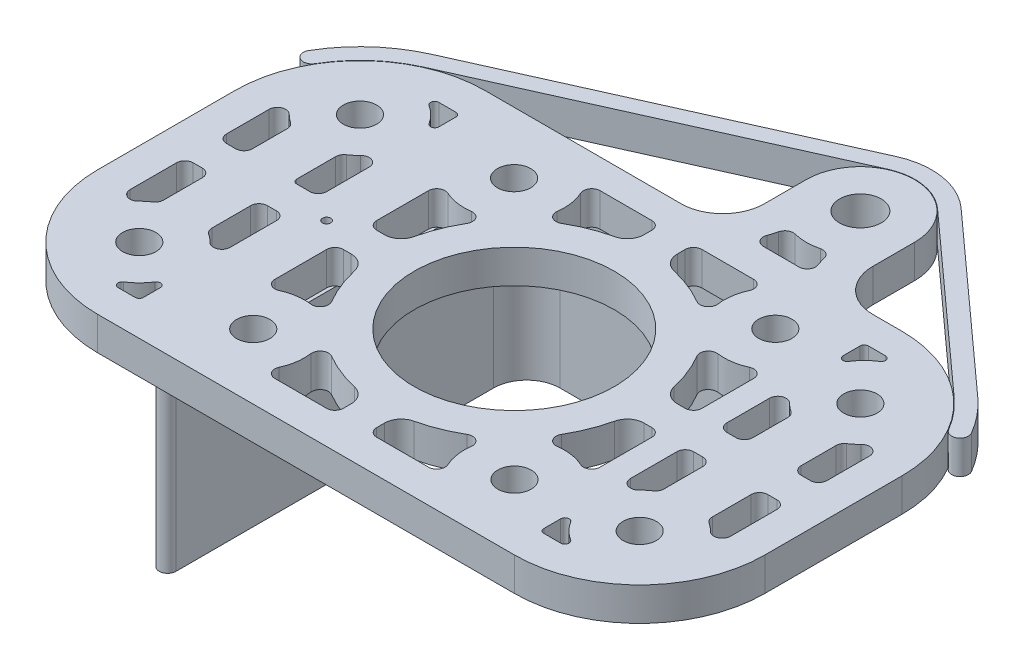
SolidWorks part; units mm, degrees
ref_plane "Front Plane" through (0, 0, 0) normal (0, 0, 1) x (1, 0, 0)
ref_plane "Top Plane" through (0, 0, 0) normal (0, 1, 0) x (1, 0, 0)
ref_plane "Right Plane" through (0, 0, 0) normal (1, 0, 0) x (0, 0, -1)
sketch "Sketch1" plane through (0, 0, 0) normal (0, 1, 0) x (1, 0, 0)
  line L1 (-21.5, 13.9196) -> (-21.5, 17.5) construction
  line L2 (-17.5, -21.5) -> (17.5, -21.5) construction
  line L3 (19.5, -3) -> (19.5, -9.2063)
  line L4 (19.5, 9.2063) -> (19.5, 3)
  line L5 (21.5, 21.5) -> (-21.5, -21.5) construction
  line L7 (-17.5, 21.5) -> (17.5, 21.5) construction
  line L8 (-11.4637, 10) -> (-11.4637, -10) construction
  line L9 (-11.4637, 10) -> (-11.4637, -10) construction
  line L10 (0, 0) -> (0, 15.6621) construction
  line L11 (0, 15.6621) -> (-15.6378, 15.6621) construction
  line L13 (-26.5, -23) -> (-3, -23)
  line L14 (0, -21.5) -> (0, 38.5) construction
  line L15 (-26.5, 23.4637) -> (23.5, 23.4637)
  line L16 (38.5, -8) -> (38.5, 8.4637)
  line L17 (21.5, -17.5) -> (21.5, 17.5) construction
  line L18 (-41.5, 8.4637) -> (-41.5, -8)
  line L19 (-31.5, 7.4637) -> (-31.5, -7) construction
  line L21 (-21.5, -21.5) -> (21.5, 21.5) construction
  line L22 (18.5, 2) -> (17.5499, 2)
  line L23 (-34.4, 7.6508) -> (-34.4, 3)
  line L27 (-28.6, 7.6508) -> (-28.6, 3)
  line L28 (-25.5, 8.5647) -> (-25.5, 3)
  line L29 (-37.5, -8.101) -> (-37.5, -3)
  line L30 (18.5, -2) -> (17.5499, -2)
  line L31 (-3, -19.5) -> (-9.2063, -19.5)
  line L32 (9.2063, -19.5) -> (3, -19.5)
  line L33 (12.6, -23) -> (12.6, -43) construction
  line L34 (2, -18.5) -> (2, -17.5499)
  line L35 (-2, -18.5) -> (-2, -17.5499)
  line L36 (-19.5, 3) -> (-19.5, 9.2063)
  line L37 (-19.5, -9.2063) -> (-19.5, -3)
  line L38 (-18.5, -2) -> (-17.5499, -2)
  line L39 (-9.2063, 19.5) -> (-3, 19.5)
  line L40 (-25.5, 16.9278) -> (-25.5, 18.9637)
  line L41 (2, 18.5) -> (2, 17.5499)
  line L42 (-2, 18.5) -> (-2, 17.5499)
  line L43 (3, 19.5) -> (9.2063, 19.5)
  line L44 (0, 23.4637) -> (0, 16) construction
  line L45 (-18.5, 2) -> (-17.5499, 2)
  line L47 (18.5, 38.5) -> (38.5, 38.5) construction
  line L48 (-26.5, -2) -> (-28.1, -2)
  line L51 (-25.5, -16.4641) -> (-25.5, -18.5)
  line L52 (-20.3267, -20.3302) -> (-20.3284, -20.3284)
  line L53 (-28.0359, -19) -> (-26, -19)
  line L54 (0, -23.4637) -> (0, -16) construction
  line L55 (-21.5, 623) -> (-21.5, -43) construction
  line L56 (18.5, -23) -> (18.5, 603) construction
  line L57 (12.8901, -37.861) -> (33.5871, -19.1693)
  line L58 (-19.5, -23) -> (-15.6, -23) construction
  line L59 (5.8213, -38.9772) -> (-32.6549, -21.7339)
  line L60 (12.6, -43) -> (12.6, -63) construction
  line L61 (-18.9133, -18.9151) -> (-18.9142, -18.9142)
  line L62 (-26.5, 2) -> (-27.6, 2)
  line L63 (-21.5, 38.5) -> (-41.5, 38.5) construction
  line L65 (-28.0359, 19.4637) -> (-26, 19.4637)
  line L66 (23, -19.4637) -> (25.0359, -19.4637)
  line L67 (-34.4, -3) -> (-34.4, -7.1871)
  line L68 (-37.5, 3) -> (-37.5, 8.5647)
  line L69 (-35.4, 2) -> (-36.5, 2)
  line L70 (-35.4, -2) -> (-36.5, -2)
  line L71 (-28.6, -2.5) -> (-28.6, -7.1871)
  line L72 (-25.5, -3) -> (-25.5, -8.101)
  line L73 (22.5, -8.101) -> (22.5, -3)
  line L74 (28.5, 7.4637) -> (28.5, -7) construction
  line L75 (-26.5, -3) -> (-18.5, 3) construction
  line L76 (-31.5, 27.4637) -> (28.5, 27.4637) construction
  line L77 (-26.5, 3) -> (-18.5, -3) construction
  line L78 (22.5, 16.9278) -> (22.5, 18.9637)
  line L79 (34.5, -8.101) -> (34.5, -3)
  line L80 (25.6, 7.6508) -> (25.6, 3)
  line L81 (31.4, 7.6508) -> (31.4, 3)
  line L82 (23, 19.4637) -> (25.0359, 19.4637)
  line L83 (22.5, -16.9278) -> (22.5, -18.9637)
  line L84 (17.5499, 2) -> (17.5499, -2) construction
  line L85 (22.5, 0) -> (25.6, 0) construction
  line L86 (23.5, -2) -> (24.6, -2)
  line L87 (23.5, 2) -> (24.6, 2)
  line L88 (-31.5, 23.4637) -> (28.5, 23.4637) construction
  line L89 (15, -33) -> (15, -28)
  line L90 (32.4, -2) -> (33.5, -2)
  line L91 (25.6, -3) -> (25.6, -7.1871)
  line L92 (28.5, 38.5) -> (28.5, 26.8752) construction
  line L93 (31.4, -3) -> (31.4, -7.1871)
  line L94 (32.4, 2) -> (33.5, 2)
  line L95 (22.5, 3) -> (22.5, 8.5647)
  line L96 (34.5, 3) -> (34.5, 8.5647)
  line L97 (2, -33) -> (2, -28)
  line L98 (20, -23) -> (23.5, -23)
  line L100 (5.0034, -40.8023) -> (-33.4728, -23.559)
  line L101 (10.6325, -23.5) -> (6.3675, -23.5)
  line L102 (14.2306, -39.3453) -> (34.9276, -20.6536)
  line L103 (9.2063, -23.5) -> (3, -23.5) construction
  arc A0 (23.5, -23) -> (38.5, -8) centre (23.5, -8) ccw
  arc A1 (38.5, 8.4637) -> (23.5, 23.4637) centre (23.5, 8.4637) ccw
  arc A2 (-26.5, 23.4637) -> (-41.5, 8.4637) centre (-26.5, 8.4637) ccw
  arc A3 (-17.5, 21.5) -> (-21.5, 17.5) centre (-17.5, 17.5) ccw construction
  arc A4 (-21.5, -17.5) -> (-17.5, -21.5) centre (-17.5, -17.5) ccw construction
  arc A5 (-41.5, -8) -> (-26.5, -23) centre (-26.5, -8) ccw
  circle A7 centre (-31.5, 13.4637) radius 2
  circle A9 centre (28.5, 13.4637) radius 2
  circle A10 centre (0, 0) radius 12
  circle A11 centre (-15.6378, 15.6621) radius 2
  circle A12 centre (15.6621, 15.6378) radius 2
  circle A13 centre (0, 0) radius 3.7
  arc A14 (21.5, -17.5) -> (17.5, -21.5) centre (17.5, -17.5) cw construction
  arc A15 (17.5, 21.5) -> (21.5, 17.5) centre (17.5, 17.5) cw construction
  circle A20 centre (15.6378, -15.6621) radius 2
  circle A21 centre (-15.6621, -15.6378) radius 2
  circle A22 centre (28.5, -13) radius 2
  circle A23 centre (-31.5, -13) radius 2
  arc A24 (-28.1571, 8.4812) -> (-27.2143, 9.2646) centre (-31.5, 13.4637) ccw
  arc A25 (-34.8429, -8.0175) -> (-35.7857, -8.8009) centre (-31.5, -13) ccw
  arc A26 (31.8429, 8.4812) -> (32.7857, 9.2646) centre (28.5, 13.4637) ccw
  arc A27 (25.1571, -8.0175) -> (24.2143, -8.8009) centre (28.5, -13) ccw
  arc A28 (-26.4231, 16.6614) -> (-28.3024, 18.5406) centre (-31.5, 13.4637) ccw
  arc A29 (-27.2143, -8.8009) -> (-28.1571, -8.0175) centre (-31.5, -13) ccw
  arc A30 (-35.7857, 9.2646) -> (-34.8429, 8.4812) centre (-31.5, 13.4637) ccw
  arc A31 (-28.3024, -18.0769) -> (-26.4231, -16.1976) centre (-31.5, -13) ccw
  arc A32 (13.7831, -8.1256) -> (15.5999, -3.5556) centre (0, 0) ccw
  arc A33 (13.7831, -8.1256) -> (14.7756, -9.6248) centre (14.6446, -8.6335) ccw
  arc A34 (18.0864, -10.1167) -> (14.7756, -9.6248) centre (15.5724, -15.6501) ccw
  arc A35 (17.5499, -2) -> (15.5999, -3.5556) centre (17.5499, -4) ccw
  arc A36 (18.0864, -10.1167) -> (19.5, -9.2063) centre (18.5, -9.2063) ccw
  arc A37 (19.5, -3) -> (18.5, -2) centre (18.5, -3) ccw
  arc A38 (18.0864, 10.1167) -> (14.7756, 9.6248) centre (15.5724, 15.6501) cw
  arc A39 (17.5499, 2) -> (15.5999, 3.5556) centre (17.5499, 4) cw
  arc A40 (13.7831, 8.1256) -> (14.7756, 9.6248) centre (14.6446, 8.6335) cw
  arc A41 (13.7831, 8.1256) -> (15.5999, 3.5556) centre (0, 0) cw
  arc A42 (18.5, 2) -> (19.5, 3) centre (18.5, 3) ccw
  arc A43 (18.0864, 10.1167) -> (19.5, 9.2063) centre (18.5, 9.2063) cw
  arc A44 (-8.1256, -13.7831) -> (-3.5556, -15.5999) centre (0, 0) ccw
  arc A45 (-10.1167, 18.0864) -> (-9.6248, 14.7756) centre (-15.6501, 15.5724) cw
  arc A46 (8.1256, 13.7831) -> (3.5556, 15.5999) centre (0, 0) ccw
  arc A47 (-8.1256, -13.7831) -> (-9.6248, -14.7756) centre (-8.6335, -14.6446) ccw
  arc A48 (8.1256, 13.7831) -> (9.6248, 14.7756) centre (8.6335, 14.6446) ccw
  arc A49 (10.1167, 18.0864) -> (9.6248, 14.7756) centre (15.6501, 15.5724) ccw
  arc A50 (2, 17.5499) -> (3.5556, 15.5999) centre (4, 17.5499) ccw
  arc A51 (-2, 17.5499) -> (-3.5556, 15.5999) centre (-4, 17.5499) cw
  arc A52 (-10.1167, -18.0864) -> (-9.6248, -14.7756) centre (-15.6501, -15.5724) ccw
  arc A53 (-8.1256, 13.7831) -> (-9.6248, 14.7756) centre (-8.6335, 14.6446) cw
  arc A54 (-2, -17.5499) -> (-3.5556, -15.5999) centre (-4, -17.5499) ccw
  arc A55 (-8.1256, 13.7831) -> (-3.5556, 15.5999) centre (0, 0) cw
  arc A56 (-10.1167, -18.0864) -> (-9.2063, -19.5) centre (-9.2063, -18.5) ccw
  arc A57 (-3, -19.5) -> (-2, -18.5) centre (-3, -18.5) ccw
  arc A58 (10.1167, -18.0864) -> (9.6248, -14.7756) centre (15.6501, -15.5724) cw
  arc A59 (2, -17.5499) -> (3.5556, -15.5999) centre (4, -17.5499) cw
  arc A60 (8.1256, -13.7831) -> (9.6248, -14.7756) centre (8.6335, -14.6446) cw
  arc A61 (8.1256, -13.7831) -> (3.5556, -15.5999) centre (0, 0) cw
  arc A62 (2, -18.5) -> (3, -19.5) centre (3, -18.5) ccw
  arc A63 (10.1167, -18.0864) -> (9.2063, -19.5) centre (9.2063, -18.5) cw
  arc A64 (-13.7831, 8.1256) -> (-15.5999, 3.5556) centre (0, 0) ccw
  arc A65 (-13.7831, 8.1256) -> (-14.7756, 9.6248) centre (-14.6446, 8.6335) ccw
  arc A66 (-18.0864, 10.1167) -> (-14.7756, 9.6248) centre (-15.5724, 15.6501) ccw
  arc A67 (-17.5499, 2) -> (-15.5999, 3.5556) centre (-17.5499, 4) ccw
  arc A68 (-18.0864, 10.1167) -> (-19.5, 9.2063) centre (-18.5, 9.2063) ccw
  arc A69 (-19.5, 3) -> (-18.5, 2) centre (-18.5, 3) ccw
  arc A70 (-18.0864, -10.1167) -> (-14.7756, -9.6248) centre (-15.5724, -15.6501) cw
  arc A71 (-17.5499, -2) -> (-15.5999, -3.5556) centre (-17.5499, -4) cw
  arc A72 (-13.7831, -8.1256) -> (-14.7756, -9.6248) centre (-14.6446, -8.6335) cw
  arc A73 (10.1167, 18.0864) -> (9.2063, 19.5) centre (9.2063, 18.5) ccw
  arc A74 (-13.7831, -8.1256) -> (-15.5999, -3.5556) centre (0, 0) cw
  arc A75 (-18.5, -2) -> (-19.5, -3) centre (-18.5, -3) ccw
  arc A76 (3, 19.5) -> (2, 18.5) centre (3, 18.5) ccw
  arc A77 (-18.0864, -10.1167) -> (-19.5, -9.2063) centre (-18.5, -9.2063) cw
  arc A78 (-2, 18.5) -> (-3, 19.5) centre (-3, 18.5) ccw
  arc A79 (-28.6, -7.1871) -> (-28.1571, -8.0175) centre (-27.6, -7.1871) ccw
  arc A80 (-10.1167, 18.0864) -> (-9.2063, 19.5) centre (-9.2063, 18.5) cw
  arc A81 (-25.5, -8.101) -> (-27.2143, -8.8009) centre (-26.5, -8.101) cw
  arc A82 (-37.5, -8.101) -> (-35.7857, -8.8009) centre (-36.5, -8.101) ccw
  arc A83 (-34.4, -7.1871) -> (-34.8429, -8.0175) centre (-35.4, -7.1871) cw
  arc A84 (-34.4, 7.6508) -> (-34.8429, 8.4812) centre (-35.4, 7.6508) ccw
  arc A85 (-28.6, 7.6508) -> (-28.1571, 8.4812) centre (-27.6, 7.6508) cw
  arc A86 (-25.5, 8.5647) -> (-27.2143, 9.2646) centre (-26.5, 8.5647) ccw
  arc A87 (-37.5, 8.5647) -> (-35.7857, 9.2646) centre (-36.5, 8.5647) cw
  arc A88 (24.6, -2) -> (25.6, -3) centre (24.6, -3) cw
  arc A89 (23.5, -2) -> (22.5, -3) centre (23.5, -3) ccw
  arc A90 (32.7857, -8.8009) -> (31.8429, -8.0175) centre (28.5, -13) ccw
  arc A91 (25.3024, 18.5406) -> (23.4231, 16.6614) centre (28.5, 13.4637) ccw
  arc A92 (25.6, -7.1871) -> (25.1571, -8.0175) centre (24.6, -7.1871) cw
  arc A93 (22.5, -8.101) -> (24.2143, -8.8009) centre (23.5, -8.101) ccw
  arc A94 (32.4, -2) -> (31.4, -3) centre (32.4, -3) ccw
  arc A95 (34.5, -3) -> (33.5, -2) centre (33.5, -3) ccw
  arc A96 (31.4, -7.1871) -> (31.8429, -8.0175) centre (32.4, -7.1871) ccw
  arc A97 (34.5, -8.101) -> (32.7857, -8.8009) centre (33.5, -8.101) cw
  arc A98 (34.5, 3) -> (33.5, 2) centre (33.5, 3) cw
  arc A99 (31.4, 7.6508) -> (31.8429, 8.4812) centre (32.4, 7.6508) cw
  arc A100 (34.5, 8.5647) -> (32.7857, 9.2646) centre (33.5, 8.5647) ccw
  arc A101 (31.4, 3) -> (32.4, 2) centre (32.4, 3) ccw
  arc A102 (23.5, 2) -> (22.5, 3) centre (23.5, 3) cw
  arc A103 (24.6, 2) -> (25.6, 3) centre (24.6, 3) ccw
  arc A104 (25.6, 7.6508) -> (25.1571, 8.4812) centre (24.6, 7.6508) ccw
  arc A105 (22.5, 8.5647) -> (24.2143, 9.2646) centre (23.5, 8.5647) cw
  arc A106 (24.2143, 9.2646) -> (25.1571, 8.4812) centre (28.5, 13.4637) ccw
  arc A107 (25.3024, -18.5406) -> (23.4231, -16.6614) centre (28.5, -13.4637) cw
  arc A108 (-27.6, 2) -> (-28.6, 3) centre (-27.6, 3) cw
  arc A109 (-34.4, -3) -> (-35.4, -2) centre (-35.4, -3) ccw
  arc A110 (-34.4, 3) -> (-35.4, 2) centre (-35.4, 3) cw
  arc A111 (-36.5, 2) -> (-37.5, 3) centre (-36.5, 3) cw
  arc A112 (-26.5, 2) -> (-25.5, 3) centre (-26.5, 3) ccw
  arc A113 (-36.5, -2) -> (-37.5, -3) centre (-36.5, -3) ccw
  arc A114 (-26.5, -2) -> (-25.5, -3) centre (-26.5, -3) cw
  arc A115 (-27.6, -2) -> (-28.6, -3) centre (-27.6, -3) ccw
  arc A116 (-28.3024, 18.5406) -> (-28.0359, 19.4637) centre (-28.0359, 18.9637) cw
  arc A117 (-25.5, 18.9637) -> (-26, 19.4637) centre (-26, 18.9637) ccw
  arc A118 (-25.5, 16.9278) -> (-26.4231, 16.6614) centre (-26, 16.9278) cw
  arc A119 (-28.3024, -18.0769) -> (-28.0359, -19) centre (-28.0359, -18.5) ccw
  arc A120 (-25.5, -18.5) -> (-26, -19) centre (-26, -18.5) cw
  arc A121 (-25.5, -16.4641) -> (-26.4231, -16.1976) centre (-26, -16.4641) ccw
  arc A122 (-28.1, -2) -> (-28.6, -2.5) centre (-28.1, -2.5) ccw
  arc A123 (22.5, 18.9637) -> (23, 19.4637) centre (23, 18.9637) cw
  arc A124 (22.5, 16.9278) -> (23.4231, 16.6614) centre (23, 16.9278) ccw
  arc A125 (25.0359, 19.4637) -> (25.3024, 18.5406) centre (25.0359, 18.9637) cw
  arc A126 (-28.1, -2) -> (-28.6, -2.5) centre (-28.1, -2.5) ccw
  arc A127 (23, -19.4637) -> (22.5, -18.9637) centre (23, -18.9637) cw
  arc A128 (25.3024, -18.5406) -> (25.0359, -19.4637) centre (25.0359, -18.9637) cw
  arc A129 (-28.1, -2) -> (-28.6, -2.5) centre (-28.1, -2.5) ccw
  arc A130 (23.4231, -16.6614) -> (22.5, -16.9278) centre (23, -16.9278) ccw
  arc A131 (-28.1, -2) -> (-28.6, -2.5) centre (-28.1, -2.5) ccw
  circle A132 centre (-22.5, 0) radius 0.5
  circle A133 centre (8.5, -33) radius 2.5 construction
  circle A134 centre (8.5, -33) radius 2.5
  arc A135 (2, -33) -> (15, -33) centre (8.5, -33) ccw
  arc A136 (10.0301, -26.6827) -> (6.9699, -26.6827) centre (8.5, -33) ccw
  arc A137 (-3, -23) -> (2, -28) centre (-3, -28) cw
  arc A138 (15, -28) -> (20, -23) centre (20, -28) cw
  arc A139 (11.239, -25.9397) -> (11.5693, -24.85) centre (20, -28) cw
  arc A140 (-3, -19) -> (3.2249, -21.5) centre (-3, -28) cw
  arc A141 (10.6325, -23.5) -> (11.5693, -24.85) centre (10.6325, -24.5) cw
  arc A142 (11, -28) -> (20, -19) centre (20, -28) cw construction
  arc A143 (5.4307, -24.85) -> (5.761, -25.9397) centre (-3, -28) cw
  arc A144 (-3, -19) -> (6, -28) centre (-3, -28) cw construction
  arc A145 (6.3675, -23.5) -> (5.4307, -24.85) centre (6.3675, -24.5) ccw
  arc A146 (6.9699, -26.6827) -> (5.761, -25.9397) centre (6.7344, -25.7108) cw
  arc A147 (10.0301, -26.6827) -> (11.239, -25.9397) centre (10.2656, -25.7108) ccw
  arc A148 (5.8213, -38.9772) -> (12.8901, -37.861) centre (8.5, -33) ccw
  arc A149 (-39.5, -15.583) -> (-32.6549, -21.7339) centre (-26.5, -8) ccw
  arc A150 (33.5871, -19.1693) -> (36.5, -15.583) centre (23.5, -8) ccw
  arc A151 (23.5, -23.05) -> (38.55, -8) centre (23.5, -8) ccw construction
  arc A152 (1.95, -33) -> (15.05, -33) centre (8.5, -33) ccw construction
  arc A153 (-41.55, -8) -> (-26.5, -23.05) centre (-26.5, -8) ccw construction
  arc A154 (-41.2276, -16.5908) -> (-33.4728, -23.559) centre (-26.5, -8) ccw
  arc A155 (5.0034, -40.8023) -> (14.2306, -39.3453) centre (8.5, -33) ccw
  arc A156 (34.9276, -20.6536) -> (38.2276, -16.5908) centre (23.5, -8) ccw
  arc A157 (-39.5, -15.583) -> (-41.2276, -16.5908) centre (-40.3638, -16.0869) ccw
  arc A158 (36.5, -15.583) -> (38.2276, -16.5908) centre (37.3638, -16.0869) cw
  point P0 (0.0699, 0.0699)
  point P5 (0, 0)
  point P51 (0, 0)
  point P98 (-25.5, -13)
  point P115 (-37.5, -13)
  point P119 (-11.2855, 11.3418)
  point P207 (0, 0)
  point P212 (-25.5, 13.4637)
  point P215 (-37.5, 13.4637)
  point P227 (0, 0)
  point P243 (37.5, 13.4637)
  point P244 (-21.5, -16.3317)
  point P253 (25.6, -2)
  point P261 (37.5, -13)
  point P275 (22.5, -13)
  point P278 (31.4, -2)
  point P287 (34.5, 2)
  point P297 (31.4, 2)
  point P306 (22.5, 13.4637)
  point P312 (-34.4, -2)
  point P315 (-34.4, 2)
  point P318 (-37.5, 2)
  point P325 (-25.5, -2)
  point P328 (-28.6, -2)
  point P335 (-25.5, 13.4637)
  point P342 (-25.5, -13)
  point P348 (22.5, 19.4637)
  point P351 (22.5, 13.4637)
  point P354 (28.5, 19.4637)
  point P360 (22.5, -19.4637)
  point P363 (28.5, -19.4637)
  point P367 (22.5, -13.4637)
  point P396 (4.7942, -23.5)
  point P407 (5.9468, -27.0225)
  dimension "D3" = 4
  dimension "D4" = 1
  dimension "D5" = 0.5
  dimension "D9" = 15
  dimension "D12" = 5
  dimension "D7" = 0.5
  dimension "D11" = 1
  dimension "D2" = 1
  dimension "D6" = 0.5
  dimension "D8" = 0.5
  dimension "D10" = 4
extrude "Boss-Extrude1" add sketch "Sketch1" along normal blind 4
sketch "Sketch2" plane through (0, 0, 0) normal (0, 1, 0) x (1, 0, 0)
  line L0 (18.5, -23) -> (18.5, 603) construction
  line L1 (18.5, -23) -> (18.5, 603) construction
  line L2 (-21.1, 623) -> (-21.1, -43)
  line L3 (-21.1, 21.4637) -> (-21.1, -16.6)
  line L4 (-26.5, 23.4637) -> (23.5, 23.4637) construction
  line L5 (-26.5, -22.6) -> (-3, -22.6)
  line L6 (-15.1, -22.6) -> (16.4993, -22.6)
  line L7 (-26.5, 23.4637) -> (23.5, 23.4637) construction
  line L8 (-19.1, 21.4637) -> (-19.1, -16.6)
  line L9 (-15.1, -20.6) -> (16.4993, -20.6)
  line L10 (-31.5, 8.4637) -> (-31.5, 5.5637) construction
  line L12 (-31.5, -8) -> (-31.5, -5.1) construction
  line L13 (-31.5, -5.1) -> (-31.5, 5.5637) construction
  line L14 (-28.6, -5.1) -> (-28.6, 5.5637) construction
  line L15 (-34.4, -5.1) -> (-34.4, 5.5637) construction
  line L16 (28.5, 5.5637) -> (28.5, -5.1) construction
  line L17 (28.5, 7.4637) -> (28.5, -7) construction
  line L18 (25.6, 5.5637) -> (25.6, -5.1) construction
  line L19 (31.4, 5.5637) -> (31.4, -5.1) construction
  arc A0 (-15.1, -22.6) -> (-21.1, -16.6) centre (-15.1, -16.6) cw
  arc A1 (-15.1, -20.6) -> (-19.1, -16.6) centre (-15.1, -16.6) cw
  arc A2 (-21.1, 21.4637) -> (-19.1, 21.4637) centre (-20.1, 21.4637) cw
  arc A3 (16.4993, -22.6) -> (16.4993, -20.6) centre (16.4993, -21.6) ccw
  circle A4 centre (-31.5, 13.4637) radius 5 construction
  circle A7 centre (-31.5, -13) radius 5 construction
  arc A8 (-28.6, -5.1) -> (-34.4, -5.1) centre (-31.5, -5.1) cw construction
  arc A9 (-28.6, 5.5637) -> (-34.4, 5.5637) centre (-31.5, 5.5637) ccw construction
  arc A10 (25.6, 5.5637) -> (31.4, 5.5637) centre (28.5, 5.5637) cw construction
  arc A11 (25.6, -5.1) -> (31.4, -5.1) centre (28.5, -5.1) ccw construction
  dimension "D3" = 6
  dimension "D5" = 2.9
  dimension "D6" = 2.9
  dimension "D1" = 0.4
  dimension "D2" = 0.4
  dimension "D4" = 2
extrude "Boss-Extrude2" add sketch "Sketch2" against normal blind 20
sketch "Sketch3" plane through (0, 0, 0) normal (0, 1, 0) x (1, 0, 0)
  line L0 (31.4, 5.5637) -> (31.4, -5.1) construction
  line L1 (25.6, 5.5637) -> (25.6, -5.1) construction
  line L2 (-28.6, -5.1) -> (-28.6, 5.5637) construction
  line L3 (-34.4, -5.1) -> (-34.4, 5.5637) construction
  line L4 (31.4, 5.5637) -> (31.4, -5.1)
  line L5 (25.6, 5.5637) -> (25.6, -5.1)
  line L6 (-28.6, -5.1) -> (-28.6, 5.5637)
  line L7 (-34.4, -5.1) -> (-34.4, 5.5637)
  line L16 (-32.4, -5.1) -> (-32.4, 5.5637)
  line L17 (-30.6, -5.1) -> (-30.6, 5.5637)
  line L18 (27.6, 5.5637) -> (27.6, -5.1)
  line L19 (29.4, 5.5637) -> (29.4, -5.1)
  arc A0 (31.4, 5.5637) -> (25.6, 5.5637) centre (28.5, 5.5637) ccw construction
  arc A1 (25.6, -5.1) -> (31.4, -5.1) centre (28.5, -5.1) ccw construction
  arc A2 (-34.4, -5.1) -> (-28.6, -5.1) centre (-31.5, -5.1) ccw construction
  arc A3 (-28.6, 5.5637) -> (-34.4, 5.5637) centre (-31.5, 5.5637) ccw construction
  arc A4 (31.4, 5.5637) -> (25.6, 5.5637) centre (28.5, 5.5637) ccw
  arc A5 (25.6, -5.1) -> (31.4, -5.1) centre (28.5, -5.1) ccw
  arc A6 (-34.4, -5.1) -> (-28.6, -5.1) centre (-31.5, -5.1) ccw
  arc A7 (-28.6, 5.5637) -> (-34.4, 5.5637) centre (-31.5, 5.5637) ccw
  arc A16 (-30.6, 5.5637) -> (-32.4, 5.5637) centre (-31.5, 5.5637) ccw
  arc A17 (-32.4, -5.1) -> (-30.6, -5.1) centre (-31.5, -5.1) ccw
  arc A18 (29.4, 5.5637) -> (27.6, 5.5637) centre (28.5, 5.5637) ccw
  arc A19 (27.6, -5.1) -> (29.4, -5.1) centre (28.5, -5.1) ccw
  dimension "D1" = 2
  dimension "D2" = 2
extrude "Boss-Extrude3" add sketch "Sketch3" against normal blind 3
ref_plane "Plane1" through (0, 51.5, 0) normal (0, 1, 0) x (1, 0, 0)
sketch "Sketch5" plane through (0, 51.5, 0) normal (0, 1, 0) x (1, 0, 0)
  line L0 (-21, 17) -> (-21, -17) construction
  line L1 (-21, -17) -> (-17, -21) construction
  line L2 (-17, -21) -> (17, -21) construction
  line L3 (17, -21) -> (21, -17) construction
  line L4 (21, -17) -> (21, 17) construction
  line L5 (21, 17) -> (17, 21) construction
  line L6 (17, 21) -> (-17, 21) construction
  line L7 (-17, 21) -> (-21, 17) construction
  line L8 (-21.5, 16.5) -> (-21.5, -16.5)
  line L9 (-21.5, 17.2071) -> (-21.5, -17.2071) construction
  line L10 (-16.5, -21.5) -> (16.5, -21.5)
  line L11 (-17.2071, -21.5) -> (17.2071, -21.5) construction
  line L12 (21.5, -16.5) -> (21.5, 16.5)
  line L13 (21.5, -17.2071) -> (21.5, 17.2071) construction
  line L14 (16.5, 21.5) -> (-16.5, 21.5)
  line L15 (17.2071, 21.5) -> (-17.2071, 21.5) construction
  line L16 (-17.2071, 21.5) -> (-21.5, 17.2071) construction
  line L17 (-21.5, -17.2071) -> (-17.2071, -21.5) construction
  line L18 (17.2071, -21.5) -> (21.5, -17.2071) construction
  line L19 (21.5, 17.2071) -> (17.2071, 21.5) construction
  circle A0 centre (0, 0) radius 12 construction
  arc A1 (-21.5, -16.5) -> (-16.5, -21.5) centre (-16.5, -16.5) ccw
  arc A2 (16.5, -21.5) -> (21.5, -16.5) centre (16.5, -16.5) ccw
  arc A3 (21.5, 16.5) -> (16.5, 21.5) centre (16.5, 16.5) ccw
  arc A4 (-16.5, 21.5) -> (-21.5, 16.5) centre (-16.5, 16.5) ccw
  dimension "D2" = 5
  dimension "D1" = 0.5
sketch "Sketch6" plane through (0, 4, 0) normal (0, 1, 0) x (1, 0, 0)
  line L4 (-41.5, 8.4637) -> (-41.5, -8)
  line L5 (-26.5, -23) -> (-3, -23)
  line L6 (38.5, -8) -> (38.5, 8.4637)
  line L7 (23.5, 23.4637) -> (-26.5, 23.4637)
  line L8 (-41.5, 8.4637) -> (-41.5, -8)
  line L9 (-26.5, -23) -> (-3, -23)
  line L10 (38.5, -8) -> (38.5, 8.4637)
  line L11 (23.5, 23.4637) -> (-26.5, 23.4637)
  line L15 (15, -33) -> (15, -28)
  line L16 (15, -33) -> (15, -28)
  line L17 (20, -23) -> (23.5, -23)
  line L18 (20, -23) -> (23.5, -23)
  line L19 (2, -28) -> (2, -33)
  line L20 (2, -28) -> (2, -33)
  arc A4 (-41.5, -8) -> (-26.5, -23) centre (-26.5, -8) ccw
  arc A5 (23.5, -23) -> (38.5, -8) centre (23.5, -8) ccw
  arc A6 (38.5, 8.4637) -> (23.5, 23.4637) centre (23.5, 8.4637) ccw
  arc A7 (-26.5, 23.4637) -> (-41.5, 8.4637) centre (-26.5, 8.4637) ccw
  arc A8 (-41.5, -8) -> (-26.5, -23) centre (-26.5, -8) ccw
  arc A9 (23.5, -23) -> (38.5, -8) centre (23.5, -8) ccw
  arc A10 (38.5, 8.4637) -> (23.5, 23.4637) centre (23.5, 8.4637) ccw
  arc A11 (-26.5, 23.4637) -> (-41.5, 8.4637) centre (-26.5, 8.4637) ccw
  arc A15 (20, -23) -> (15, -28) centre (20, -28) ccw
  arc A16 (20, -23) -> (15, -28) centre (20, -28) ccw
  arc A17 (2, -28) -> (-3, -23) centre (-3, -28) ccw
  arc A18 (2, -28) -> (-3, -23) centre (-3, -28) ccw
  arc A19 (2, -33) -> (15, -33) centre (8.5, -33) ccw
  arc A20 (2, -33) -> (15, -33) centre (8.5, -33) ccw
  dimension "D1" = 0
mirror "Mirror1" about plane through (0, 4, -23.4637) normal (0, 0, -1) of bodies 127 130
delete or keep bodies "Body-Delete/Keep 1" type delete bodies bodies 127 130
